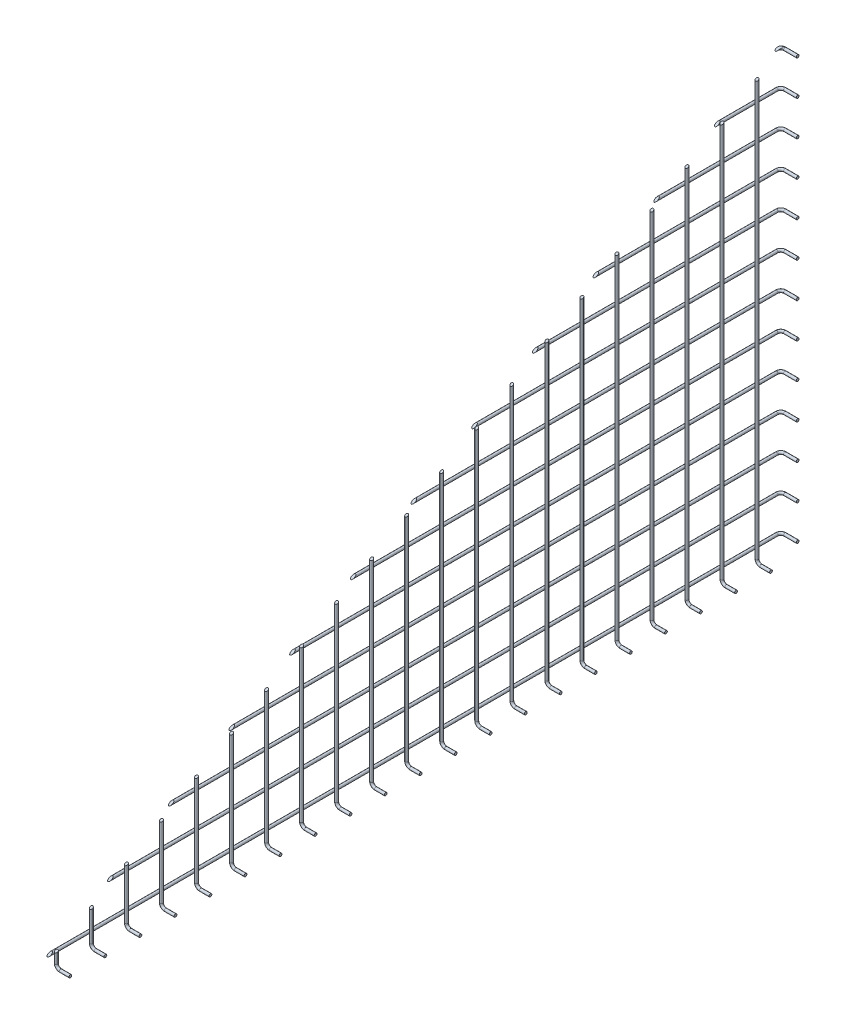
SolidWorks part; units mm, degrees
material "AISI 1020"
ref_plane "Спереди" through (0, 0, 0) normal (0, 0, 1) x (1, 0, 0)
ref_plane "Сверху" through (0, 0, 0) normal (0, 1, 0) x (1, 0, 0)
ref_plane "Справа" through (0, 0, 0) normal (1, 0, 0) x (0, 0, -1)
sketch "Эскиз1" plane through (0, 0, 0) normal (0, 0, 1) x (1, 0, 0)
  line L0 (20, 2) -> (6, 2)
  line L1 (20, -50) -> (20, 2650.6738) construction
  line L2 (0, 8) -> (0, 890)
  line L3 (-6, 875) -> (-1.25, 875) construction
  line L4 (22, 0) -> (-22, 0) construction
  arc A0 (6, 2) -> (0, 8) centre (6, 8) cw
  point P11 (13, 2)
  dimension "D3" = 6
  dimension "D1" = 15
  dimension "D2" = 2
ref_plane "Плоскость1" through (20, 0, 0) normal (1, 0, 0) x (0, 0, -1)
sketch "Эскиз2" plane through (20, 0, 0) normal (1, 0, 0) x (0, 0, -1)
  circle A0 centre (0, 2) radius 2
  dimension "D1" = 4
sweep "По траектории1" add profiles "Эскиз2" path "Эскиз1"
pattern_linear "Линейный массив2" count 11 spacing 50 along (0, 0, -1) of bodies 103
pattern_linear "Линейный массив3" count 11 spacing 50 along (0, 0, 1) of bodies 103
ref_plane "Плоскость2" through (0, 20, 0) normal (0, 1, 0) x (1, 0, 0)
sketch "Эскиз3" plane through (0, 20, 0) normal (0, 1, 0) x (1, 0, 0)
  line L0 (20, 538) -> (2, 538)
  line L1 (2, -538) -> (20, -538)
  line L2 (-4, -532) -> (-4, 532)
  line L3 (20, 700.1025) -> (20, -1090) construction
  line L4 (-22, 540) -> (22, 540) construction
  line L5 (-22, -540) -> (22, -540) construction
  circle A0 centre (0, 500) radius 2 construction
  arc A1 (2, 538) -> (-4, 532) centre (2, 532) ccw
  arc A2 (2, -538) -> (-4, -532) centre (2, -532) cw
  dimension "D1" = 2
  dimension "D4" = 6
  dimension "D2" = 2
  dimension "D3" = 2
sketch "Эскиз4" plane through (20, 0, 0) normal (1, 0, 0) x (0, 0, -1)
  circle A0 centre (538, 20) radius 2
  dimension "D1" = 4
sweep "По траектории2" add profiles "Эскиз4" path "Эскиз3"
pattern_linear "Линейный массив4" count 18 spacing 50 along (0, 1, 0) of "По траектории2"
sketch "Эскиз5" plane through (0, 0, 0) normal (1, 0, 0) x (0, 0, -1)
  line L0 (-540, 0) -> (540, 0)
  line L2 (540, 0) -> (540, 623.5383)
  line L3 (540, 623.5383) -> (-540, 0)
  line L4 (-676.6025, -78.8675) -> (1090, 941.0809) construction
  line L5 (-540, 0) -> (540, 0) construction
  line L8 (540, -2050) -> (540, 623.5383) construction
  point P9 (536, 620)
  point P10 (0, 0)
  point P11 (545, 626.425)
extrude "Вырез-Вытянуть1" cut sketch "Эскиз5" against normal through all both and the other way through all flip side to cut
